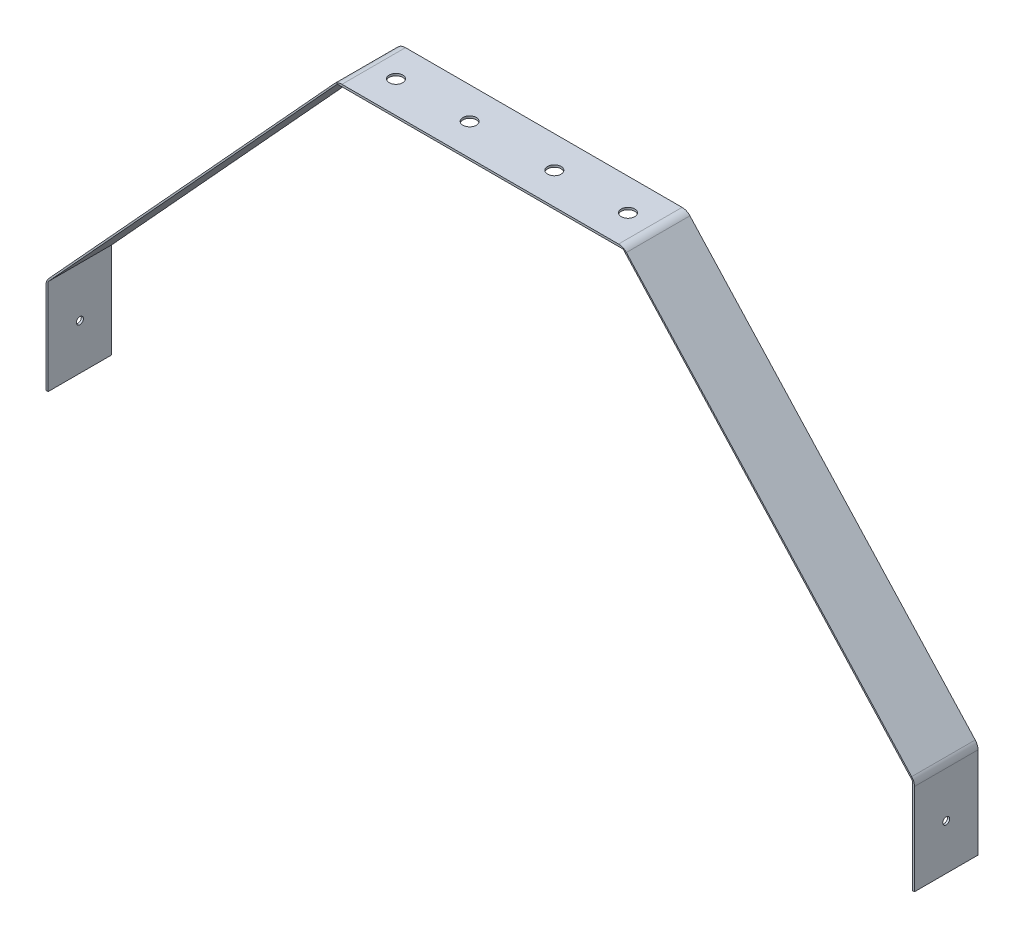
SolidWorks part; units mm, degrees
material "Thornel Mat VMA"
ref_plane "Front Plane" through (0, 0, 0) normal (0, 0, 1) x (1, 0, 0)
ref_plane "Top Plane" through (0, 0, 0) normal (0, 1, 0) x (1, 0, 0)
ref_plane "Right Plane" through (0, 0, 0) normal (1, 0, 0) x (0, 0, -1)
sketch "Sketch1" plane through (0, 0, 0) normal (0, 0, 1) x (1, 0, 0)
  line L1 (-205, 97.5) -> (205, 97.5)
  line L2 (-205, 97.5) -> (-205, -97.5)
  line L3 (-205, -97.5) -> (205, -97.5)
  line L4 (205, 97.5) -> (205, -97.5)
  line L5 (-205, 97.5) -> (205, -97.5) construction
  line L6 (-205, -97.5) -> (205, 97.5) construction
  point P0 (0, 0)
extrude "Boss-Extrude1" add sketch "Sketch1" along normal blind 30
sketch "Sketch2" plane through (0, 0, 30) normal (0, 0, 1) x (1, 0, 0)
  line L1 (-205, 97.5) -> (-205, -97.5) construction
  line L5 (205, 97.5) -> (-205, 97.5) construction
  line L8 (-205, -52.5) -> (-205, -97.5)
  line L9 (205, -97.5) -> (205, 97.5) construction
  line L10 (205, -52.5) -> (67.5, 97.5)
  line L11 (-205, -52.5) -> (-67.5, 97.5)
  line L12 (-205, -97.5) -> (205, -97.5)
  line L13 (205, -52.5) -> (67.5, 97.5)
  line L15 (205, -97.5) -> (205, -52.5)
  line L16 (67.5, 97.5) -> (-67.5, 97.5)
  line M13 (205, -97.5) -> (205, 97.5)
  line M14 (205, 97.5) -> (-205, 97.5)
  line M15 (-205, 97.5) -> (-205, -97.5)
extrude "Cut-Extrude1" cut sketch "Sketch2" against normal blind 30 contours L11 M15 M14 | L10 M13 M14
sketch "Sketch3" plane through (0, 0, 30) normal (0, 0, 1) x (1, 0, 0)
  line L0 (-205, -97.5) -> (-204, -97.5)
  line L1 (-205, -97.5) -> (205, -97.5) construction
  line L3 (-204, -52.5) -> (-40.8942, 125.5423)
  line L5 (-204, -97.5) -> (-204, -52.5)
  line L6 (-67.5, 97.5) -> (-67.5, 96.5)
  line L7 (-67.5, 96.5) -> (67.5, 96.5)
  line L8 (67.5, 97.5) -> (67.5, 96.5)
  line L10 (205, -97.5) -> (204, -97.5)
  line L11 (204, -97.5) -> (204, -52.5)
  line L12 (204, -52.5) -> (67.5, 96.5)
  line M7 (-205, -97.5) -> (205, -97.5)
extrude "Cut-Extrude2" cut sketch "Sketch3" against normal blind 30 contours L11 L12 L7 L3 L5 M7
fillet "Fillet1" radius 5 1 edges at (-205, -52.5, 15)
fillet "Fillet4" radius 5 1 edges at (-67.5, 97.5, 15)
fillet "Fillet5" radius 5 1 edges at (67.5, 97.5, 15)
fillet "Fillet6" radius 5 1 edges at (205, -52.5, 15)
ref_plane "Plane1" through (205, 0, 0) normal (1, 0, 0) x (0, 0, -1)
sketch "Sketch4" plane through (205, 0, 0) normal (1, 0, 0) x (0, 0, -1)
  line L0 (-15, -97.5) -> (-15, -52.2848) construction
  line L1 (-30, -97.5) -> (0, -97.5) construction
  line L2 (-30, -75.9725) -> (0, -75.9725) construction
  line L5 (-30, -97.5) -> (-30, -54.4449) construction
  line L6 (0, -97.5) -> (0, -54.4449) construction
  circle A0 centre (-15, -75.9725) radius 1.65
  dimension "D1" = 3.3
extrude "Cut-Extrude3" cut sketch "Sketch4" against normal through all
ref_plane "Plane2" through (0, 97.5, 0) normal (0, 1, 0) x (1, 0, 0)
sketch "Sketch5" plane through (0, 97.5, 0) normal (0, 1, 0) x (1, 0, 0)
  line L0 (-64.4681, -15) -> (64.4681, -15) construction
  line L1 (-67.5, -30) -> (67.5, -30) construction
  line L3 (0, 0) -> (0, -30) construction
  circle A2 centre (-20, -15) radius 3.175
  circle A3 centre (20, -15) radius 3.175
  circle A4 centre (54.7688, -15) radius 3.175
  circle A5 centre (-54.7687, -15) radius 3.175
  point P17 (0, -15)
  point P18 (0, -15)
  dimension "D1" = 6.35
  dimension "D2" = 6.35
  dimension "D3" = 20
  dimension "D5" = 6.35
  dimension "D6" = 6.35
  dimension "D4" = 20
  dimension "D7" = 109.5375
  dimension "D8" = 34.7688
extrude "Cut-Extrude4" cut sketch "Sketch5" against normal blind 10
